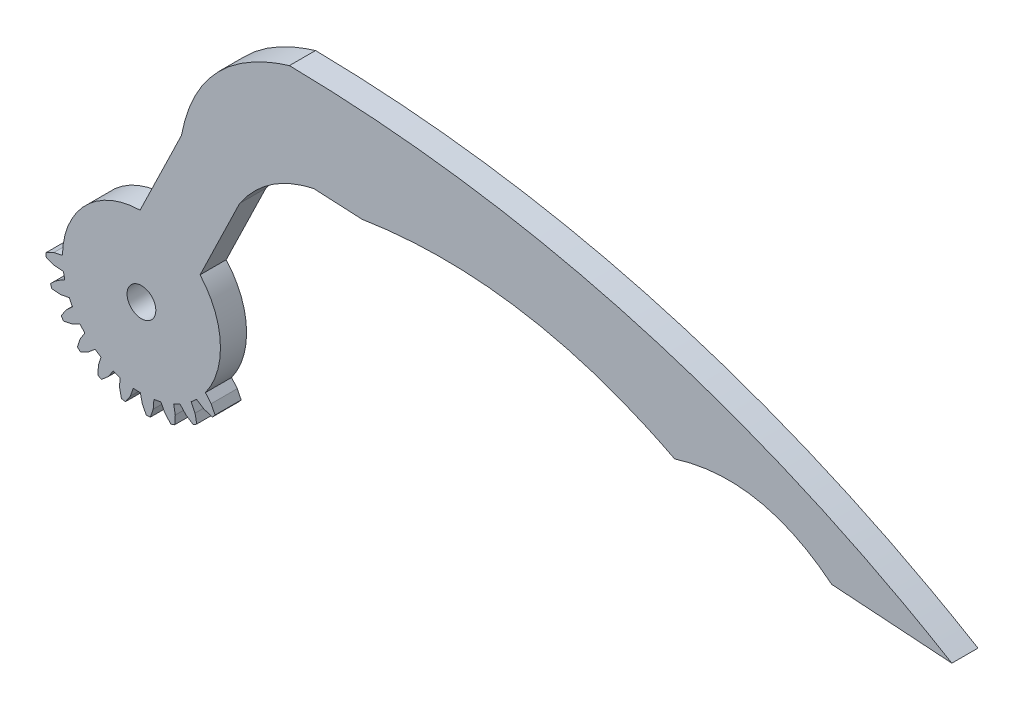
SolidWorks part; units mm, degrees
material "ABS"
ref_plane "Front Plane" through (0, 0, 0) normal (0, 0, 1) x (1, 0, 0)
ref_plane "Top Plane" through (0, 0, 0) normal (0, 1, 0) x (1, 0, 0)
ref_plane "Right Plane" through (0, 0, 0) normal (1, 0, 0) x (0, 0, -1)
sketch "Sketch1" plane through (0, 0, 0) normal (0, 0, 1) x (1, 0, 0)
  line L1 (-75, -35) -> (75, -35)
  line L2 (-75, -35) -> (-75, 35)
  line L3 (-75, 35) -> (75, 35)
  line L4 (75, -35) -> (75, 35)
  line L5 (-75, -35) -> (75, 35) construction
  line L6 (-75, 35) -> (75, -35) construction
  point P0 (0, 0)
  dimension "D1" = 150
  dimension "D2" = 70
extrude "Boss-Extrude2" add sketch "Sketch1" along normal blind 4
sketch "Sketch3" plane through (0, 0, 4) normal (0, 0, 1) x (1, 0, 0)
  line L0 (-46.1081, -8.4538) -> (-40.0487, 4.0474)
  line L1 (-55.2898, -4.4698) -> (-48.9602, 8.589)
  line L2 (50.5625, -1.1502) -> (68.9467, -2.3983)
  line L3 (50.5625, -1.1502) -> (68.9467, -2.3983) construction
  line L4 (-28.6885, 11.676) -> (-21.3304, 11.3024)
  line L5 (-45.2892, -23.657) -> (-44.4133, -24.6811)
  line L6 (-44.4133, -24.6811) -> (-43.8182, -25.8903)
  line L7 (-43.8182, -25.8903) -> (-44.2265, -26.3624)
  line L8 (-44.2265, -26.3624) -> (-45.5131, -25.9455)
  line L9 (-45.5131, -25.9455) -> (-46.6483, -25.2283)
  line L10 (-46.6483, -25.2283) -> (-47.4595, -25.9495)
  line L11 (-47.4595, -25.9495) -> (-46.8785, -27.1655)
  line L12 (-46.8785, -27.1655) -> (-46.6166, -28.4874)
  line L13 (-46.6166, -28.4874) -> (-47.1332, -28.8377)
  line L14 (-47.1332, -28.8377) -> (-48.2644, -28.1052)
  line L15 (-48.2644, -28.1052) -> (-49.179, -27.1154)
  line L16 (-49.179, -27.1154) -> (-50.1492, -27.6022)
  line L17 (-50.1492, -27.6022) -> (-49.9027, -28.9271)
  line L18 (-49.9027, -28.9271) -> (-49.9918, -30.2718)
  line L19 (-49.9918, -30.2718) -> (-50.5815, -30.4764)
  line L20 (-50.5815, -30.4764) -> (-51.4846, -29.4761)
  line L21 (-51.4846, -29.4761) -> (-52.1119, -28.2833)
  line L22 (-52.1119, -28.2833) -> (-53.175, -28.5024)
  line L23 (-53.175, -28.5024) -> (-53.2797, -29.8459)
  line L24 (-53.2797, -29.8459) -> (-53.7139, -31.1217)
  line L25 (-53.7139, -31.1217) -> (-54.3365, -31.1668)
  line L26 (-54.3365, -31.1668) -> (-54.9499, -29.9668)
  line L27 (-54.9499, -29.9668) -> (-55.2471, -28.6524)
  line L28 (-55.2471, -28.6524) -> (-56.3306, -28.5887)
  line L29 (-56.3306, -28.5887) -> (-56.7796, -29.8594)
  line L30 (-56.7796, -29.8594) -> (-57.5292, -30.9794)
  line L31 (-57.5292, -30.9794) -> (-58.1422, -30.8618)
  line L32 (-58.1422, -30.8618) -> (-58.4241, -29.5439)
  line L33 (-58.4241, -29.5439) -> (-58.3709, -28.1973)
  line L34 (-58.3709, -28.1973) -> (-59.4011, -27.8555)
  line L35 (-59.4011, -27.8555) -> (-60.1636, -28.9666)
  line L36 (-60.1636, -28.9666) -> (-61.1776, -29.8544)
  line L37 (-61.1776, -29.8544) -> (-61.7392, -29.5822)
  line L38 (-61.7392, -29.5822) -> (-61.6705, -28.2363)
  line L39 (-61.6705, -28.2363) -> (-61.2706, -26.9493)
  line L40 (-61.2706, -26.9493) -> (-62.1772, -26.3524)
  line L41 (-62.1772, -26.3524) -> (-63.2013, -27.2284)
  line L42 (-63.2013, -27.2284) -> (-64.4105, -27.8235)
  line L43 (-64.4105, -27.8235) -> (-64.8825, -27.4152)
  line L44 (-64.8825, -27.4152) -> (-64.4678, -26.1329)
  line L45 (-64.4678, -26.1329) -> (-63.7485, -24.9933)
  line L46 (-63.7485, -24.9933) -> (-64.4697, -24.1822)
  line L47 (-64.4697, -24.1822) -> (-65.6856, -24.7632)
  line L48 (-65.6856, -24.7632) -> (-67.0076, -25.0251)
  line L49 (-67.0076, -25.0251) -> (-67.3579, -24.5085)
  line L50 (-67.3579, -24.5085) -> (-66.6254, -23.3773)
  line L51 (-66.6254, -23.3773) -> (-65.6356, -22.4627)
  line L52 (-65.6356, -22.4627) -> (-66.1223, -21.4925)
  line L53 (-66.1223, -21.4925) -> (-67.4424, -21.7387)
  line L54 (-67.4424, -21.7387) -> (-68.7919, -21.6498)
  line L55 (-68.7919, -21.6498) -> (-68.9966, -21.0602)
  line L56 (-68.9966, -21.0602) -> (-68.2949, -20.3812)
  line L57 (-68.2949, -20.3812) -> (-67.4824, -19.8397)
  line L58 (-67.4824, -19.8397) -> (-66.8165, -19.4782)
  line L59 (-66.8165, -19.4782) -> (-67.0225, -18.4667)
  line L60 (-67.0225, -18.4667) -> (-68.3661, -18.3619)
  line L61 (-68.3661, -18.3619) -> (-69.6419, -17.9278)
  line L62 (-69.6419, -17.9278) -> (-69.687, -17.3052)
  line L63 (-69.687, -17.3052) -> (-68.487, -16.6918)
  line L64 (-68.487, -16.6918) -> (-67.1725, -16.3946)
  arc A0 (-43.8182, -25.8903) -> (-45.2892, -23.657) centre (-48.9228, -27.6517) ccw construction
  arc A1 (-46.6483, -25.2283) -> (-44.2361, -26.3605) centre (-43.2187, -21.0572) ccw construction
  arc A2 (-46.6166, -28.4874) -> (-47.4595, -25.9495) centre (-52.0032, -28.8676) ccw construction
  arc A3 (-49.179, -27.1154) -> (-47.1332, -28.8377) centre (-44.7867, -23.9742) ccw construction
  arc A4 (-49.9918, -30.2718) -> (-50.1492, -27.6022) centre (-55.2933, -29.2448) ccw construction
  arc A6 (-52.1119, -28.2833) -> (-50.5815, -30.4764) centre (-47.0562, -26.3859) ccw construction
  arc A7 (-53.7139, -31.1217) -> (-53.175, -28.5024) centre (-58.5689, -28.7577) ccw construction
  arc A8 (-55.2471, -28.6524) -> (-54.3365, -31.1668) centre (-49.8726, -28.1281) ccw construction
  arc A9 (-57.5292, -30.9794) -> (-56.3306, -28.5887) centre (-61.6069, -27.4393) ccw construction
  arc A10 (-58.3709, -28.1973) -> (-58.1422, -30.8618) centre (-53.0439, -29.082) ccw construction
  arc A11 (-61.1776, -29.8544) -> (-59.4011, -27.8555) centre (-64.2001, -25.3796) ccw construction
  arc A12 (-61.2706, -26.9493) -> (-61.7392, -29.5822) centre (-56.354, -29.1826) ccw construction
  arc A13 (-64.4105, -27.8235) -> (-62.1772, -26.3524) centre (-66.1718, -22.7189) ccw construction
  arc A14 (-63.7485, -24.9933) -> (-64.8825, -27.4152) centre (-59.5774, -28.423) ccw construction
  arc A15 (-67.0076, -25.0251) -> (-64.4697, -24.1822) centre (-67.3878, -19.6385) ccw construction
  arc A16 (-65.6356, -22.4627) -> (-67.3579, -24.5085) centre (-62.4944, -26.855) ccw construction
  arc A17 (-68.7824, -21.6517) -> (-66.1223, -21.4925) centre (-67.765, -16.3484) ccw construction
  arc A18 (-67.4824, -19.8397) -> (-68.9966, -21.0602) centre (-64.9061, -24.5855) ccw construction
  arc A19 (-69.6419, -17.9278) -> (-67.0225, -18.4667) centre (-67.2778, -13.0727) ccw construction
  arc A20 (-67.1725, -16.3946) -> (-69.687, -17.3052) centre (-66.6483, -21.7691) ccw construction
  arc A21 (-46.1081, -8.4538) -> (-45.2892, -23.657) centre (-55.0809, -16.5607) cw
  arc A22 (-67.1725, -16.3946) -> (-55.2898, -4.4698) centre (-55.0809, -16.5607) cw
  arc A23 (-55.2898, -4.4698) -> (-67.1725, -16.3946) centre (-55.0809, -16.5607) ccw construction
  circle A24 centre (-55.0809, -16.5607) radius 2.2
  spline S0 degree 3 poles (-40.0487, 4.0474) (-39.104, 5.4432) (-37.348, 7.4486) (-33.5293, 10.1849) (-30.6851, 11.2528) (-28.6885, 11.676) knots 0 0 0 0 0.360826 0.563284 1 1 1 1
  spline S1 degree 2 poles (-28.6885, 11.676) (-35.9285, 10.1196) (-40.0487, 4.0474) knots 0 0 0 1 1 1 weights 1 1 1 construction
  spline S2 degree 3 poles (-21.3304, 11.3024) (-17.6224, 11.891) (-11.6396, 12.4293) (-3.4063, 12.1977) (3.4698, 11.3781) (9.9345, 9.9744) (17.7912, 7.5395) (23.0987, 5.2284) (26.52, 3.462) knots 0 0 0 0 0.228339 0.364249 0.50023 0.648901 0.765884 1 1 1 1
  spline S3 degree 2 poles (-6.0093, 12.242) (-13.5679, 12.5331) (-21.3304, 11.3024) knots 0.605436 0.605436 0.605436 0.878376 0.878376 0.878376 weights 1 1 1 construction
  spline S4 degree 2 poles (-5.7849, 12.233) (10.8626, 11.5417) (26.52, 3.462) knots 0.398618 0.398618 0.398618 1 1 1 weights 1 1 1 construction
  spline S5 degree 3 poles (26.52, 3.462) (29.2935, 4.3362) (33.4859, 5.0503) (39.243, 4.4996) (44.67, 2.9152) (48.4146, 0.5918) (50.5625, -1.1502) knots 0 0 0 0 0.341962 0.489689 0.675604 1 1 1 1
  spline S6 degree 2 poles (26.52, 3.462) (39.7432, 7.6067) (50.5625, -1.1502) knots 0 0 0 1 1 1 weights 1 1 1 construction
  spline S7 degree 3 poles (-48.9602, 8.589) (-48.525, 10.9272) (-47.3515, 14.5083) (-44.5417, 18.7009) (-41.7024, 21.4978) (-37.7233, 24.1714) (-34.4811, 25.4866) (-32.4337, 26.1156) knots 0 0 0 0 0.280485 0.437899 0.590544 0.747359 1 1 1 1
  spline S8 degree 2 poles (-32.4337, 26.1156) (-46.4795, 21.8036) (-48.9602, 8.589) knots 0 0 0 1 1 1 weights 1 1 1 construction
  spline S9 degree 3 poles (-32.4337, 26.1156) (-28.4484, 26.0523) (-22.3883, 25.795) (-14.1863, 25.0991) (-7.9809, 24.3834) (-1.111, 23.3801) (5.2646, 22.2189) (11.4337, 20.8805) (16.4021, 19.6629) (22.1, 18.1092) (28.28, 16.2164) (35.0581, 13.8606) (41.974, 11.177) (49.1365, 8.0793) (58.3459, 3.6364) (64.9024, 0.0153) (68.9467, -2.3983) knots 0 0 0 0 0.112226 0.17071 0.231734 0.288076 0.366168 0.414142 0.465798 0.510181 0.580418 0.647733 0.712182 0.789246 0.867393 1 1 1 1
  spline S10 degree 2 poles (-32.4337, 26.1156) (22.6302, 25.2404) (68.9467, -2.3983) knots 0.00235 0.00235 0.00235 1 1 1 weights 1 1 1 construction
  spline S11 degree 2 poles (68.9467, -2.3983) (22.6302, 25.2404) (-32.4337, 26.1156) knots 0 0 0 0.99765 0.99765 0.99765 weights 1 1 1 construction
  line M1 (75, -35) -> (75, 35)
  line M2 (75, 35) -> (-75, 35)
  line M3 (-75, 35) -> (-75, -35)
  line M4 (-75, -35) -> (75, -35)
extrude "Cut-Extrude2" cut sketch "Sketch3" against normal blind 4 contours S7 S9 L2 S5 S2 L4 S0 L0 A21 L5 L6 L7 L8 L9 L10 L11 L12 L13 L14 L15 L16 L17 L18 L19 L20 L21 L22 L23 L24 L25 L26 L27 L28 L29 L30 L31 L32 L33 L34 L35 L36 L37 L38 L39 L40 L41 M4 M1 M2 M3 | A24
